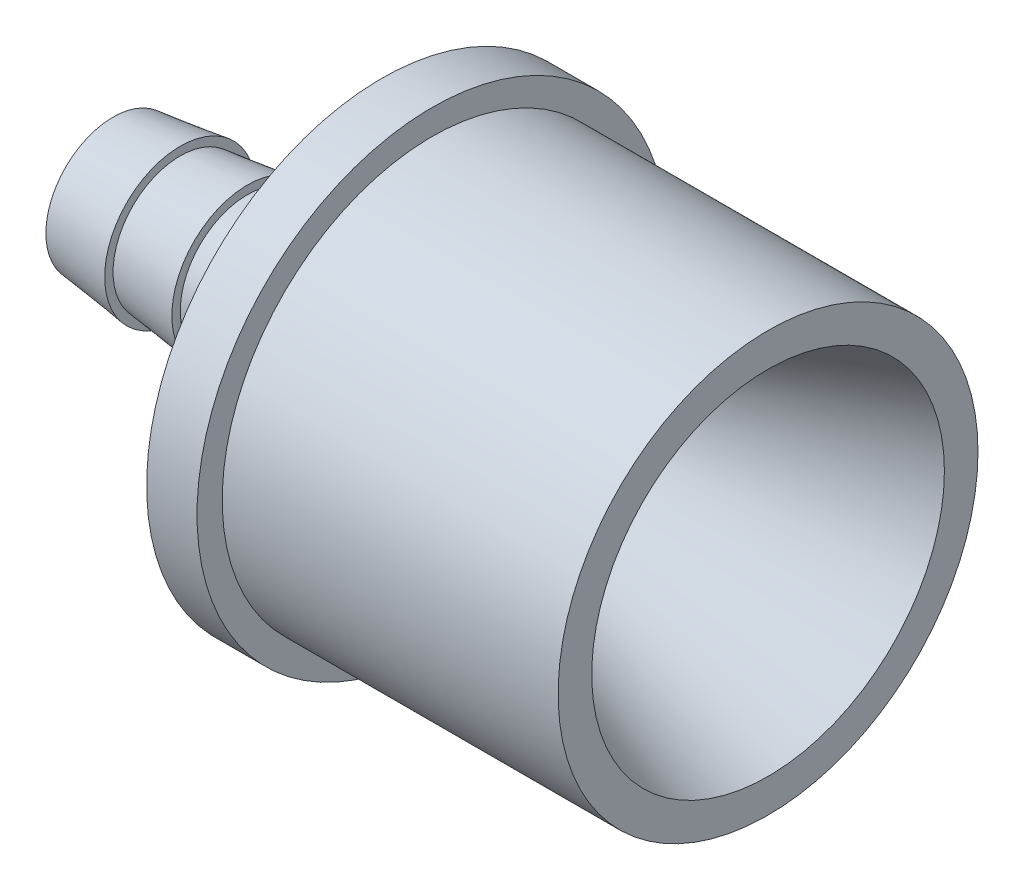
SolidWorks part; units mm, degrees
ref_plane "Front Plane" through (0, 0, 0) normal (0, 0, 1) x (1, 0, 0)
ref_plane "Top Plane" through (0, 0, 0) normal (0, 1, 0) x (1, 0, 0)
ref_plane "Right Plane" through (0, 0, 0) normal (1, 0, 0) x (0, 0, -1)
sketch "Esboço1" plane through (0, 0, 0) normal (0, 0, 1) x (1, 0, 0)
  line L0 (48.3217, 0) -> (-46.0439, 0) construction
  line L4 (-27.3234, 14) -> (-27.3234, 12.5)
  line L5 (-27.3234, 12.5) -> (-7.3234, 12.5)
  line L6 (-7.3234, 12.5) -> (-7.3234, 10.5)
  line L7 (-7.3234, 10.5) -> (-29.1152, 2.5)
  line L8 (-29.1152, 2.5) -> (-46.3234, 2.5)
  line L9 (-46.3234, 2.5) -> (-46.3234, 4)
  line L10 (-46.3234, 4) -> (-42.3234, 4.5)
  line L11 (-42.3234, 4.5) -> (-42.3234, 4)
  line L12 (-46.3234, 4) -> (1.1389, 4) construction
  line L13 (-42.3234, 4) -> (-38.3234, 4.5)
  line L14 (-38.3234, 4.5) -> (-38.3234, 4)
  line L15 (-38.3234, 4) -> (-34.3234, 4.5)
  line L16 (-34.3234, 4.5) -> (-34.3234, 4)
  line L17 (-34.3234, 4) -> (-30.3234, 4.5)
  line L22 (-30.3234, 4.5) -> (-30.3234, 14)
  line L24 (-30.3234, 14) -> (-27.3234, 14)
  line L26 (-30.3234, 4.5) -> (-30.3234, 4) [skipped]
  point P3 (-42.7133, -1.5896)
  dimension "D1" = 1.5
  dimension "D2" = 4
  dimension "D3" = 0.5
  dimension "D4" = 4
  dimension "D6" = 12.5
  dimension "D7" = 2
  dimension "D8" = 20
  dimension "D9" = 3
  dimension "D10" = 1.5
  dimension "D5" = 4
revolve "Revolução1" add sketch "Esboço1" angle 360 about L0
